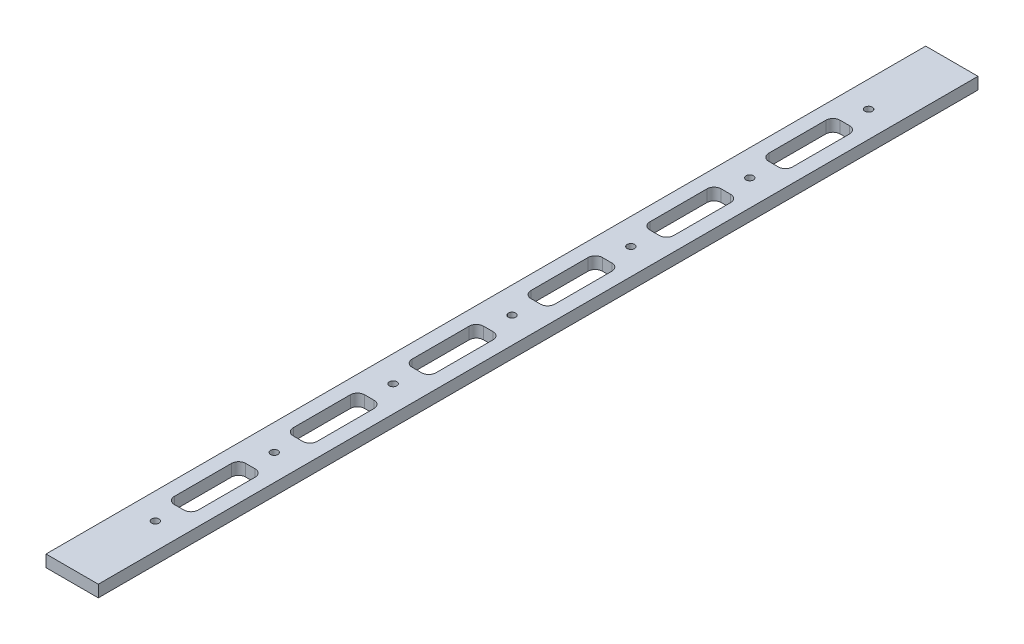
SolidWorks part; units mm, degrees
material "Thornel Mat VMA"
ref_plane "前视基准面" through (0, 0, 0) normal (0, 0, 1) x (1, 0, 0)
ref_plane "上视基准面" through (0, 0, 0) normal (0, 1, 0) x (1, 0, 0)
ref_plane "右视基准面" through (0, 0, 0) normal (1, 0, 0) x (0, 0, -1)
sketch "草图1" plane through (0, 0, 0) normal (0, 1, 0) x (1, 0, 0)
  line L1 (-11, -185) -> (11, -185)
  line L2 (-11, -185) -> (-11, 185)
  line L3 (-11, 185) -> (11, 185)
  line L4 (11, -185) -> (11, 185)
  line L5 (-11, -185) -> (11, 185) construction
  line L6 (-11, 185) -> (11, -185) construction
  point P0 (0, 0)
  dimension "D1" = 22
  dimension "D2" = 370
extrude "凸台-拉伸1" add sketch "草图1" along normal blind 5
sketch "草图2" plane through (0, 5, 0) normal (0, 1, 0) x (1, 0, 0)
  line L0 (0, 185) -> (0, -185) construction
  line L1 (11, 185) -> (-11, 185) construction
  line L2 (-11, -185) -> (11, -185) construction
  line L3 (-11, 0) -> (11, 0) construction
  line L4 (-11, 185) -> (-11, -185) construction
  line L5 (11, -185) -> (11, 185) construction
  circle A0 centre (0, 0) radius 1.55
  circle A1 centre (0, 50) radius 1.55
  circle A2 centre (0, 100) radius 1.55
  circle A3 centre (0, 150) radius 1.55
  circle A6 centre (0, -150) radius 1.55
  circle A7 centre (0, -100) radius 1.55
  circle A8 centre (0, -50) radius 1.55
  circle A9 centre (0, 200) radius 1.55 [skipped]
  point P31 (0, 0)
  point P32 (0, 0)
  point P33 (0, 0)
  dimension "D1" = 3.1
  dimension "D2" = 5
extrude "切除-拉伸1" cut sketch "草图2" against normal blind 5
sketch "草图3" plane through (0, 5, 0) normal (0, 1, 0) x (1, 0, 0)
  line L0 (0, 185) -> (0, -185) construction
  line L1 (11, 185) -> (-11, 185) construction
  line L2 (-11, -185) -> (11, -185) construction
  line L3 (-5, 63) -> (-5, 87)
  line L4 (-2, 110) -> (2, 110)
  line L5 (-5, 113) -> (-5, 137)
  line L6 (-2, 140) -> (2, 140)
  line L7 (5, 113) -> (5, 137)
  line L8 (-5, 110) -> (5, 140) construction
  line L9 (-5, 140) -> (5, 110) construction
  line L10 (-2, 60) -> (2, 60)
  line L11 (5, 63) -> (5, 87)
  line L12 (-2, 90) -> (2, 90)
  line L13 (-5, 13) -> (-5, 37)
  line L14 (-2, 10) -> (2, 10)
  line L15 (5, 13) -> (5, 37)
  line L16 (-2, 40) -> (2, 40)
  line L17 (-5, -37) -> (-5, -13)
  line L18 (-2, -40) -> (2, -40)
  line L19 (5, -37) -> (5, -13)
  line L20 (-2, -10) -> (2, -10)
  line L21 (-5, -87) -> (-5, -63)
  line L22 (-2, -90) -> (2, -90)
  line L23 (5, -87) -> (5, -63)
  line L24 (-2, -60) -> (2, -60)
  line L25 (-5, -137) -> (-5, -113)
  line L26 (-2, -140) -> (2, -140)
  line L27 (5, -137) -> (5, -113)
  line L28 (-2, -110) -> (2, -110)
  line L37 (-5, -237) -> (-5, -213) [skipped]
  line L38 (-2, -210) -> (2, -210) [skipped]
  line L39 (5, -237) -> (5, -213) [skipped]
  line L40 (-2, -240) -> (2, -240) [skipped]
  line L41 (5, -187) -> (5, -163) [skipped]
  line L42 (-5, -187) -> (-5, -163) [skipped]
  line L43 (-2, -160) -> (2, -160) [skipped]
  line L44 (-2, -190) -> (2, -190) [skipped]
  arc A1 (2, 110) -> (5, 113) centre (2, 113) ccw
  arc A2 (-2, 110) -> (-5, 113) centre (-2, 113) cw
  arc A3 (2, 140) -> (5, 137) centre (2, 137) cw
  arc A4 (-5, 137) -> (-2, 140) centre (-2, 137) cw
  arc A5 (-5, 87) -> (-2, 90) centre (-2, 87) cw
  arc A6 (-2, 60) -> (-5, 63) centre (-2, 63) cw
  arc A7 (2, 60) -> (5, 63) centre (2, 63) ccw
  arc A8 (2, 90) -> (5, 87) centre (2, 87) cw
  arc A9 (-5, 37) -> (-2, 40) centre (-2, 37) cw
  arc A10 (-2, 10) -> (-5, 13) centre (-2, 13) cw
  arc A11 (2, 10) -> (5, 13) centre (2, 13) ccw
  arc A12 (2, 40) -> (5, 37) centre (2, 37) cw
  arc A13 (-5, -13) -> (-2, -10) centre (-2, -13) cw
  arc A14 (-2, -40) -> (-5, -37) centre (-2, -37) cw
  arc A15 (2, -40) -> (5, -37) centre (2, -37) ccw
  arc A16 (2, -10) -> (5, -13) centre (2, -13) cw
  arc A17 (-5, -63) -> (-2, -60) centre (-2, -63) cw
  arc A18 (-2, -90) -> (-5, -87) centre (-2, -87) cw
  arc A19 (2, -90) -> (5, -87) centre (2, -87) ccw
  arc A20 (2, -60) -> (5, -63) centre (2, -63) cw
  arc A21 (-5, -113) -> (-2, -110) centre (-2, -113) cw
  arc A22 (-2, -140) -> (-5, -137) centre (-2, -137) cw
  arc A23 (2, -140) -> (5, -137) centre (2, -137) ccw
  arc A24 (2, -110) -> (5, -113) centre (2, -113) cw
  circle A33 centre (0, 150) radius 1.55 construction
  arc A34 (-5, -213) -> (-2, -210) centre (-2, -213) cw [skipped]
  arc A35 (2, -210) -> (5, -213) centre (2, -213) cw [skipped]
  arc A36 (2, -240) -> (5, -237) centre (2, -237) ccw [skipped]
  arc A37 (-2, -240) -> (-5, -237) centre (-2, -237) cw [skipped]
  arc A38 (-5, -163) -> (-2, -160) centre (-2, -163) cw [skipped]
  arc A39 (2, -160) -> (5, -163) centre (2, -163) cw [skipped]
  arc A40 (2, -190) -> (5, -187) centre (2, -187) ccw [skipped]
  arc A41 (-2, -190) -> (-5, -187) centre (-2, -187) cw [skipped]
  point P6 (0, 125)
  point P25 (0, 0)
  dimension "D4" = 3
  dimension "D1" = 25
  dimension "D2" = 30
  dimension "D3" = 10
  dimension "D5" = 8
extrude "切除-拉伸2" cut sketch "草图3" against normal blind 5
